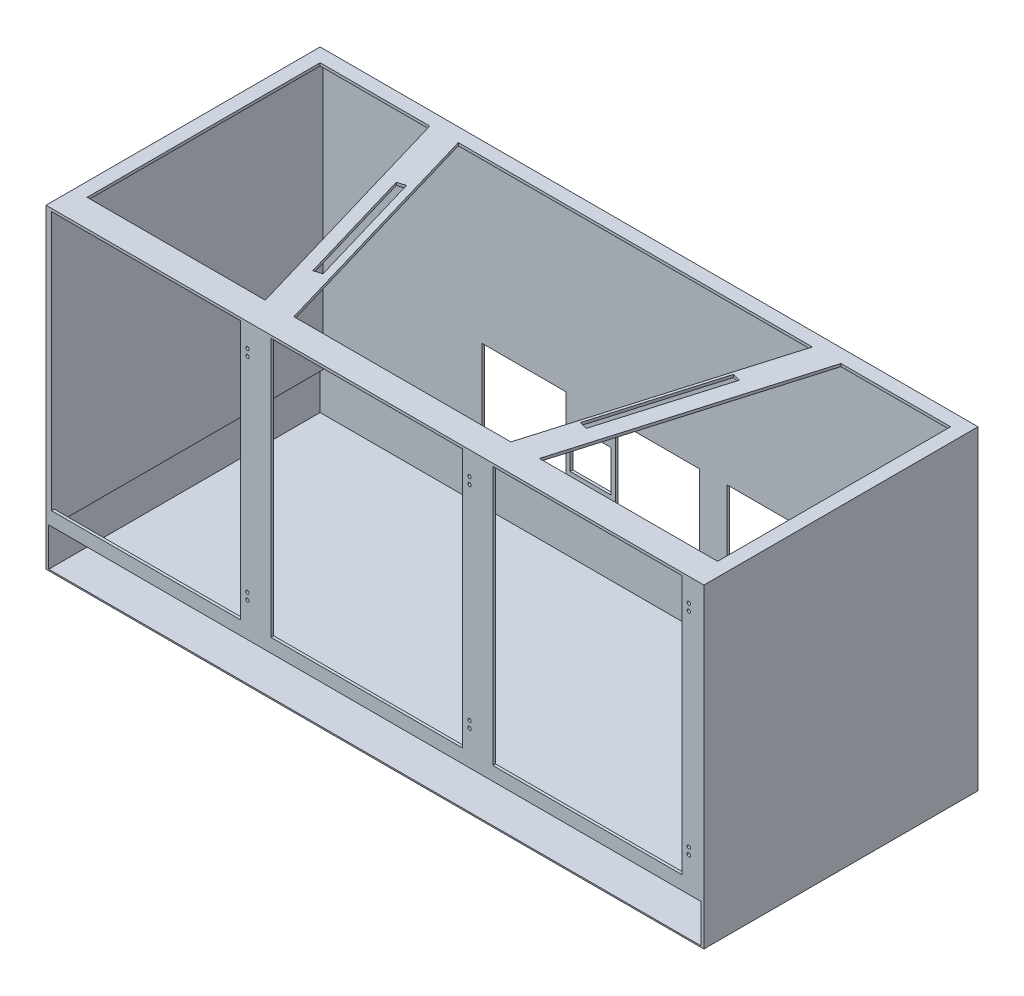
SolidWorks part; units mm, degrees
material "6061 Alloy"
ref_plane "Front Plane" through (0, 0, 0) normal (0, 0, 1) x (1, 0, 0)
ref_plane "Top Plane" through (0, 0, 0) normal (0, 1, 0) x (1, 0, 0)
ref_plane "Right Plane" through (0, 0, 0) normal (1, 0, 0) x (0, 0, -1)
sketch "Sketch1" plane through (0, 0, 0) normal (0, 1, 0) x (1, 0, 0)
  line L1 (-304.8, -127) -> (304.8, -127)
  line L2 (-304.8, -127) -> (-304.8, 127)
  line L3 (-304.8, 127) -> (304.8, 127)
  line L4 (304.8, -127) -> (304.8, 127)
  line L5 (-304.8, -127) -> (304.8, 127) construction
  line L6 (-304.8, 127) -> (304.8, -127) construction
  point P0 (0, 0)
  dimension "D1" = 609.6
  dimension "D2" = 254
extrude "Boss-Extrude1" add sketch "Sketch1" against normal blind 292.1
sketch "Sketch2" plane through (0, 0, 127) normal (0, 0, 1) x (1, 0, 0)
  line L0 (-304.8, -292.1) -> (304.8, -292.1) construction
  line L1 (-302.26, -255.27) -> (302.26, -255.27)
  line L2 (-302.26, -255.27) -> (-302.26, -290.83)
  line L3 (-302.26, -290.83) -> (302.26, -290.83)
  line L4 (302.26, -255.27) -> (302.26, -290.83)
  line L5 (304.8, -292.1) -> (304.8, 0) construction
  line L6 (-304.8, -292.1) -> (-304.8, 0) construction
  dimension "D1" = 1.27
  dimension "D2" = 2.54
  dimension "D3" = 2.54
  dimension "D4" = 35.56
extrude "Cut-Extrude1" cut sketch "Sketch2" against normal blind 251.46
sketch "Sketch3" plane through (0, 0, 127) normal (0, 0, 1) x (1, 0, 0)
  line L0 (-304.8, -292.1) -> (-304.8, 0) construction
  line L1 (-299.72, -2.54) -> (-124.46, -2.54)
  line L2 (-299.72, -2.54) -> (-299.72, -242.57)
  line L3 (-299.72, -242.57) -> (-124.46, -242.57)
  line L4 (-124.46, -2.54) -> (-124.46, -242.57)
  line L5 (-304.8, 0) -> (304.8, 0) construction
  line L6 (302.26, -255.27) -> (-302.26, -255.27) construction
  line L7 (-96.52, -2.54) -> (81.28, -2.54)
  line L8 (-96.52, -2.54) -> (-96.52, -242.57)
  line L9 (-96.52, -242.57) -> (81.28, -242.57)
  line L10 (81.28, -2.54) -> (81.28, -242.57)
  line L11 (109.22, -2.54) -> (284.48, -2.54)
  line L12 (109.22, -2.54) -> (109.22, -242.57)
  line L13 (109.22, -242.57) -> (284.48, -242.57)
  line L14 (284.48, -2.54) -> (284.48, -242.57)
  line L15 (304.8, -292.1) -> (304.8, 0) construction
  dimension "D1" = 5.08
  dimension "D2" = 2.54
  dimension "D3" = 180.34
  dimension "D4" = 12.7
  dimension "D5" = 27.94
  dimension "D6" = 27.94
  dimension "D7" = 20.32
  dimension "D8" = 177.8
extrude "Cut-Extrude2" cut sketch "Sketch3" against normal blind 251.46
sketch "Sketch4" plane through (-299.72, 0, 0) normal (1, 0, 0) x (0, 0, -1)
  line L0 (-127, -292.1) -> (127, -292.1) construction
  line L1 (-124.46, -2.54) -> (124.46, -2.54)
  line L2 (-124.46, -2.54) -> (-124.46, -242.57)
  line L3 (-124.46, -242.57) -> (124.46, -242.57)
  line L4 (124.46, -2.54) -> (124.46, -242.57)
  line L5 (-127, -292.1) -> (-127, 0) construction
  line L6 (127, -292.1) -> (127, 0) construction
  line L7 (139.7, 0) -> (-139.7, 0) construction
  dimension "D1" = 49.53
  dimension "D2" = 2.54
  dimension "D3" = 2.54
  dimension "D4" = 2.54
extrude "Cut-Extrude3" cut sketch "Sketch4" along normal blind 599.44
sketch "Sketch5" plane through (0, 0, 0) normal (0, 1, 0) x (1, 0, 0)
  line L0 (304.8, 127) -> (-304.8, 127) construction
  line L1 (-292.1, 114.3) -> (-190.5, 114.3)
  line L2 (-292.1, 114.3) -> (-292.1, -101.6)
  line L5 (-304.8, -127) -> (304.8, -127) construction
  line L6 (-304.8, 127) -> (-304.8, -127) construction
  line L7 (-190.5, 114.3) -> (-127, -101.6)
  line L17 (-164.0242, 114.3) -> (-100.5242, -101.6)
  line L18 (-292.1, -101.6) -> (-127, -101.6)
  line L20 (0, -139.7) -> (0, 139.7) construction
  line L21 (292.1, 114.3) -> (292.1, -101.6)
  line L22 (292.1, -101.6) -> (127, -101.6)
  line L23 (190.5, 114.3) -> (127, -101.6)
  line L24 (292.1, 114.3) -> (190.5, 114.3)
  line L25 (164.0242, 114.3) -> (100.5242, -101.6)
  line L26 (-164.0242, 114.3) -> (164.0242, 114.3)
  line L27 (100.5242, -101.6) -> (-100.5242, -101.6)
  dimension "D1" = 12.7
  dimension "D2" = 25.4
  dimension "D3" = 12.7
  dimension "D4" = 12.7
  dimension "D9" = 114.3
  dimension "D10" = 177.8
  dimension "D11" = 25.4
  dimension "D12" = 25.4
extrude "Cut-Extrude4" cut sketch "Sketch5" against normal up to surface (242.57 mm away) up to face at (36.2857, -242.57, 89.9886)
sketch "Sketch6" plane through (0, 0, -124.46) normal (0, 0, 1) x (1, 0, 0)
  line L0 (-299.72, -242.57) -> (-124.46, -242.57) construction
  line L1 (-152.4, -242.57) -> (-74.5744, -242.57)
  line L2 (-152.4, -242.57) -> (-152.4, -160.274)
  line L3 (-152.4, -160.274) -> (-74.5744, -160.274)
  line L4 (-74.5744, -242.57) -> (-74.5744, -160.274)
  line L5 (-96.52, -242.57) -> (81.28, -242.57) construction
  line L6 (-28.6512, -242.57) -> (49.1744, -242.57)
  line L7 (-28.6512, -242.57) -> (-28.6512, -160.274)
  line L8 (-28.6512, -160.274) -> (49.1744, -160.274)
  line L9 (49.1744, -242.57) -> (49.1744, -160.274)
  line L10 (-299.72, -242.57) -> (299.72, -242.57) construction
  line L11 (74.5744, -242.57) -> (152.4, -242.57)
  line L12 (74.5744, -242.57) -> (74.5744, -160.274)
  line L13 (74.5744, -160.274) -> (152.4, -160.274)
  line L14 (152.4, -242.57) -> (152.4, -160.274)
  line L15 (-304.8, -292.1) -> (-304.8, 0) construction
  line L16 (304.8, -292.1) -> (304.8, 0) construction
  line L18 (-70.6628, -184.15) -> (-32.5628, -184.15)
  line L19 (-70.6628, -184.15) -> (-70.6628, -222.25)
  line L20 (-70.6628, -222.25) -> (-32.5628, -222.25)
  line L21 (-32.5628, -184.15) -> (-32.5628, -222.25)
  dimension "D1" = 77.8256
  dimension "D2" = 77.8256
  dimension "D3" = 77.8256
  dimension "D4" = 82.296
  dimension "D5" = 152.4
  dimension "D6" = 152.4
  dimension "D7" = 25.4
  dimension "D8" = 38.1
  dimension "D9" = 38.1
  dimension "D10" = 3.9116
  dimension "D11" = 20.32
extrude "Cut-Extrude5" cut sketch "Sketch6" against normal through all
sketch "Sketch12" plane through (0, -255.27, 0) normal (0, -1, 0) x (1, 0, 0)
  line L1 (-299.72, 124.46) -> (299.72, 124.46)
  line L2 (-299.72, 124.46) -> (-299.72, -124.46)
  line L3 (-299.72, -124.46) -> (299.72, -124.46)
  line L4 (299.72, 124.46) -> (299.72, -124.46)
  line L6 (299.72, 124.46) -> (299.72, -124.46) construction
  line L7 (152.4, -124.46) -> (299.72, -124.46) construction
  dimension "D1" = 599.44
  dimension "D2" = 248.92
extrude "Cut-Extrude8" cut sketch "Sketch12" against normal blind 12.7
sketch "Sketch13" plane through (0, 0, 124.46) normal (0, 0, -1) x (-1, 0, 0)
  line L0 (-109.22, -242.57) -> (-284.48, -242.57) construction
  line L3 (0, 139.7) -> (0, -139.7) construction
  circle A0 centre (-295.275, -248.92) radius 3.175
  circle A1 centre (-276.225, -248.92) radius 3.175
  circle A2 centre (-257.175, -248.92) radius 3.175
  circle A3 centre (-238.125, -248.92) radius 3.175
  circle A4 centre (-219.075, -248.92) radius 3.175
  circle A5 centre (-200.025, -248.92) radius 3.175
  circle A6 centre (-180.975, -248.92) radius 3.175
  circle A7 centre (-161.925, -248.92) radius 3.175
  circle A8 centre (-142.875, -248.92) radius 3.175
  circle A9 centre (-123.825, -248.92) radius 3.175
  circle A10 centre (-104.775, -248.92) radius 3.175
  circle A11 centre (-85.725, -248.92) radius 3.175
  circle A12 centre (-66.675, -248.92) radius 3.175
  circle A13 centre (-47.625, -248.92) radius 3.175
  circle A14 centre (-28.575, -248.92) radius 3.175
  circle A15 centre (-9.525, -248.92) radius 3.175
  circle A16 centre (9.525, -248.92) radius 3.175
  circle A17 centre (28.575, -248.92) radius 3.175
  circle A18 centre (47.625, -248.92) radius 3.175
  circle A19 centre (66.675, -248.92) radius 3.175
  circle A20 centre (85.725, -248.92) radius 3.175
  circle A21 centre (104.775, -248.92) radius 3.175
  circle A22 centre (123.825, -248.92) radius 3.175
  circle A23 centre (142.875, -248.92) radius 3.175
  circle A24 centre (161.925, -248.92) radius 3.175
  circle A25 centre (180.975, -248.92) radius 3.175
  circle A26 centre (200.025, -248.92) radius 3.175
  circle A27 centre (219.075, -248.92) radius 3.175
  circle A28 centre (238.125, -248.92) radius 3.175
  circle A29 centre (257.175, -248.92) radius 3.175
  circle A30 centre (276.225, -248.92) radius 3.175
  circle A31 centre (295.275, -248.92) radius 3.175
  dimension "D1" = 6.35
  dimension "D4" = 6.35
  dimension "D5" = 6.35
  dimension "D6" = 6.35
  dimension "D7" = 6.35
  dimension "D8" = 6.35
  dimension "D9" = 6.35
  dimension "D10" = 6.35
  dimension "D11" = 6.35
  dimension "D12" = 6.35
  dimension "D13" = 6.35
  dimension "D14" = 6.35
  dimension "D26" = 6.35
  dimension "D27" = 6.35
  dimension "D28" = 6.35
  dimension "D32" = 6.35
  dimension "D2" = 6.35
  dimension "D15" = 19.05
  dimension "D16" = 19.05
  dimension "D17" = 19.05
  dimension "D18" = 19.05
  dimension "D19" = 19.05
  dimension "D20" = 19.05
  dimension "D21" = 19.05
  dimension "D22" = 19.05
  dimension "D23" = 19.05
  dimension "D24" = 19.05
  dimension "D25" = 19.05
  dimension "D29" = 19.05
  dimension "D30" = 19.05
  dimension "D31" = 19.05
  dimension "D33" = 19.05
  dimension "D34" = 9.525
extrude "Cut-Extrude9" cut sketch "Sketch13" against normal blind 1.27
sketch "Sketch14" plane through (0, 0, -124.46) normal (0, 0, 1) x (1, 0, 0)
  line L2 (0, -139.7) -> (0, 139.7) construction
  line L3 (302.26, -255.27) -> (-302.26, -255.27) construction
  circle A0 centre (-295.275, -248.92) radius 3.175
  circle A1 centre (-276.225, -248.92) radius 3.175
  circle A2 centre (-257.175, -248.92) radius 3.175
  circle A3 centre (-238.125, -248.92) radius 3.175
  circle A4 centre (-219.075, -248.92) radius 3.175
  circle A5 centre (-200.025, -248.92) radius 3.175
  circle A6 centre (-180.975, -248.92) radius 3.175
  circle A7 centre (-161.925, -248.92) radius 3.175
  circle A8 centre (-142.875, -248.92) radius 3.175
  circle A9 centre (-123.825, -248.92) radius 3.175
  circle A10 centre (-104.775, -248.92) radius 3.175
  circle A11 centre (-85.725, -248.92) radius 3.175
  circle A12 centre (-66.675, -248.92) radius 3.175
  circle A13 centre (-47.625, -248.92) radius 3.175
  circle A14 centre (-28.575, -248.92) radius 3.175
  circle A15 centre (-9.525, -248.92) radius 3.175
  circle A32 centre (9.525, -248.92) radius 3.175
  circle A33 centre (28.575, -248.92) radius 3.175
  circle A34 centre (47.625, -248.92) radius 3.175
  circle A35 centre (66.675, -248.92) radius 3.175
  circle A36 centre (85.725, -248.92) radius 3.175
  circle A37 centre (104.775, -248.92) radius 3.175
  circle A38 centre (123.825, -248.92) radius 3.175
  circle A39 centre (142.875, -248.92) radius 3.175
  circle A40 centre (161.925, -248.92) radius 3.175
  circle A41 centre (180.975, -248.92) radius 3.175
  circle A42 centre (200.025, -248.92) radius 3.175
  circle A43 centre (219.075, -248.92) radius 3.175
  circle A44 centre (238.125, -248.92) radius 3.175
  circle A45 centre (257.175, -248.92) radius 3.175
  circle A46 centre (276.225, -248.92) radius 3.175
  circle A47 centre (295.275, -248.92) radius 3.175
  dimension "D1" = 6.35
  dimension "D2" = 6.35
  dimension "D3" = 6.35
  dimension "D4" = 6.35
  dimension "D5" = 6.35
  dimension "D6" = 6.35
  dimension "D7" = 6.35
  dimension "D8" = 6.35
  dimension "D9" = 6.35
  dimension "D10" = 6.35
  dimension "D11" = 6.35
  dimension "D12" = 6.35
  dimension "D24" = 6.35
  dimension "D25" = 6.35
  dimension "D26" = 6.35
  dimension "D30" = 6.35
  dimension "D13" = 19.05
  dimension "D14" = 19.05
  dimension "D15" = 19.05
  dimension "D16" = 19.05
  dimension "D17" = 19.05
  dimension "D18" = 19.05
  dimension "D19" = 19.05
  dimension "D20" = 19.05
  dimension "D21" = 19.05
  dimension "D22" = 19.05
  dimension "D23" = 19.05
  dimension "D27" = 19.05
  dimension "D28" = 19.05
  dimension "D29" = 19.05
  dimension "D31" = 19.05
  dimension "D32" = 6.35
  dimension "D33" = 9.525
extrude "Cut-Extrude10" cut sketch "Sketch14" against normal blind 1.27
sketch "Sketch15" plane through (0, 0, 127) normal (0, 0, 1) x (1, 0, 0)
  line L0 (-124.46, -242.57) -> (-124.46, -2.54) construction
  line L1 (-304.8, 0) -> (304.8, 0) construction
  line L2 (-124.46, -122.555) -> (359.5771, -122.555) construction
  line L3 (81.28, -242.57) -> (81.28, -2.54) construction
  line L4 (284.48, -242.57) -> (284.48, -2.54) construction
  circle A0 centre (-118.11, -21.59) radius 1.5875
  circle A1 centre (-118.11, -27.94) radius 1.5875
  circle A2 centre (87.63, -21.59) radius 1.5875
  circle A3 centre (87.63, -27.94) radius 1.5875
  circle A4 centre (290.83, -21.59) radius 1.5875
  circle A5 centre (290.83, -27.94) radius 1.5875
  circle A6 centre (290.83, -217.17) radius 1.5875
  circle A7 centre (290.83, -223.52) radius 1.5875
  circle A8 centre (87.63, -217.17) radius 1.5875
  circle A9 centre (87.63, -223.52) radius 1.5875
  circle A10 centre (-118.11, -217.17) radius 1.5875
  circle A11 centre (-118.11, -223.52) radius 1.5875
  dimension "D1" = 3.175
  dimension "D2" = 3.175
  dimension "D6" = 3.175
  dimension "D7" = 3.175
  dimension "D11" = 3.175
  dimension "D12" = 3.175
  dimension "D3" = 6.35
  dimension "D4" = 6.35
  dimension "D5" = 21.59
  dimension "D8" = 6.35
  dimension "D9" = 21.59
  dimension "D10" = 6.35
  dimension "D13" = 6.35
  dimension "D14" = 21.59
  dimension "D15" = 6.35
extrude "Cut-Extrude11" cut sketch "Sketch15" against normal blind 6.35
sketch "Sketch16" plane through (0, 0, 0) normal (0, 1, 0) x (1, 0, 0)
  line L5 (149.4961, 55.9028) -> (117.2445, -53.7527)
  line L6 (117.2445, -53.7527) -> (124.5549, -55.9028)
  line L7 (124.5549, -55.9028) -> (156.8065, 53.7527)
  line L8 (156.8065, 53.7527) -> (149.4961, 55.9028)
  line L9 (149.4961, 55.9028) -> (117.2445, -53.7527)
  line L10 (117.2445, -53.7527) -> (124.5549, -55.9028)
  line L11 (124.5549, -55.9028) -> (156.8065, 53.7527)
  line L12 (156.8065, 53.7527) -> (149.4961, 55.9028)
  line L13 (-160.9397, 53.7527) -> (-128.6881, -55.9028)
  line L14 (-153.6294, 55.9028) -> (-160.9397, 53.7527)
  line L15 (-121.3777, -53.7527) -> (-153.6294, 55.9028)
  line L16 (-128.6881, -55.9028) -> (-121.3777, -53.7527)
  line L17 (-160.9397, 53.7527) -> (-128.6881, -55.9028)
  line L18 (-153.6294, 55.9028) -> (-160.9397, 53.7527)
  line L19 (-121.3777, -53.7527) -> (-153.6294, 55.9028)
  line L20 (-128.6881, -55.9028) -> (-121.3777, -53.7527)
  dimension "D1" = 0
  dimension "D2" = 0
extrude "Cut-Extrude13" cut sketch "Sketch16" against normal blind 2.54
